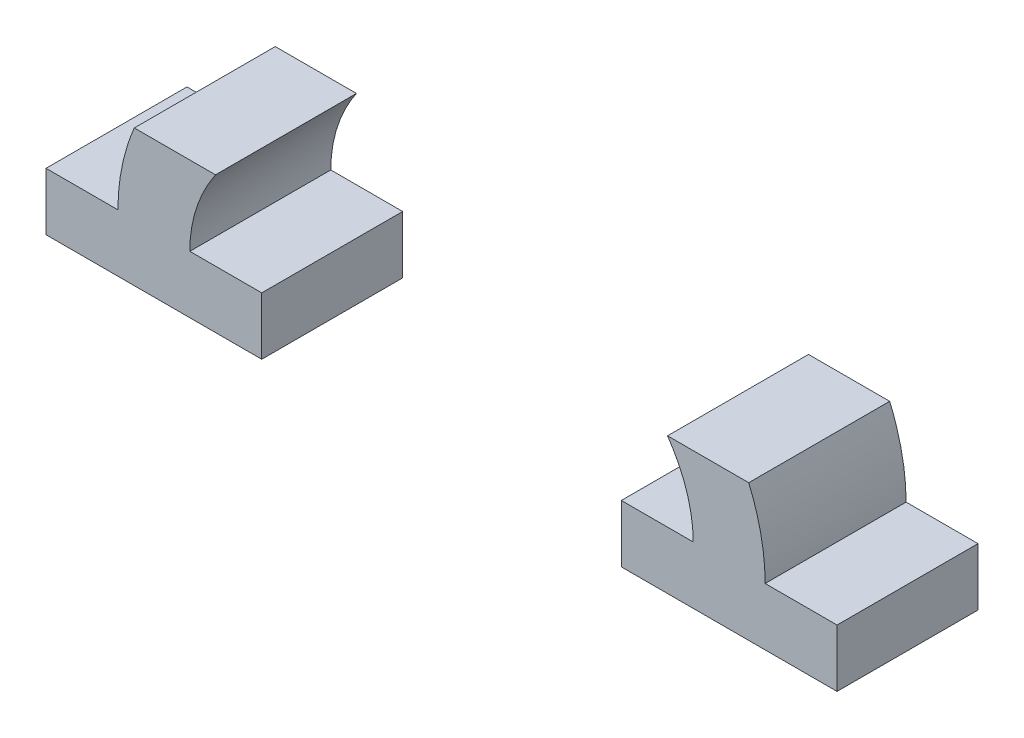
SolidWorks part; units mm, degrees
ref_plane "Front Plane" through (0, 0, 0) normal (0, 0, 1) x (1, 0, 0)
ref_plane "Top Plane" through (0, 0, 0) normal (0, 1, 0) x (1, 0, 0)
ref_plane "Right Plane" through (0, 0, 0) normal (1, 0, 0) x (0, 0, -1)
sketch "Sketch1" plane through (0, 0, 0) normal (0, 0, 1) x (1, 0, 0)
  line L0 (0, 51.691) -> (0, -47.0269) construction
  line L1 (-21.4685, 7.5) -> (-37.5, 7.5) construction
  line L2 (37.5, 7.5) -> (21.4685, 7.5) construction
  line L17 (21.3598, 7.5) -> (15.7146, 7.5)
  line L22 (-15.7146, 7.5) -> (-21.3598, 7.5)
  line L33 (-21.3177, 7.6) -> (-37.6, 7.6)
  line L34 (-27.5, 2) -> (-22.5004, 2)
  line L35 (-27.5, -2) -> (-27.5, 2)
  line L36 (-12.5, -2) -> (-27.5, -2)
  line L37 (-12.5, 2) -> (-12.5, -2)
  line L38 (-17.5006, 2) -> (-12.5, 2)
  line L39 (15.6458, 7.6) -> (-15.6458, 7.6)
  line L40 (12.5, 2) -> (17.5006, 2)
  line L41 (12.5, -2) -> (12.5, 2)
  line L42 (27.5, -2) -> (12.5, -2)
  line L43 (27.5, 2) -> (27.5, -2)
  line L44 (22.5004, 2) -> (27.5, 2)
  line L45 (37.6, 7.6) -> (21.3177, 7.6)
  line L46 (37.6, -7.6) -> (37.6, 7.6)
  line L47 (-37.6, -7.6) -> (37.6, -7.6)
  line L48 (-37.6, 7.6) -> (-37.6, -7.6)
  line L50 (-27.5, 2) -> (-22.5004, 2)
  line L51 (-27.5, -2) -> (-27.5, 2)
  line L52 (-12.5, -2) -> (-27.5, -2)
  line L53 (-12.5, 2) -> (-12.5, -2)
  line L54 (-17.5006, 2) -> (-12.5, 2)
  line L56 (12.5, 2) -> (17.5006, 2)
  line L57 (12.5, -2) -> (12.5, 2)
  line L58 (27.5, -2) -> (12.5, -2)
  line L59 (27.5, 2) -> (27.5, -2)
  line L60 (22.5004, 2) -> (27.5, 2)
  spline S8 degree 3 poles (-3020.5383, 97.1532) (36.7378, -43.2321) (-23.617, -18.6289) (-22.4681, 2.9598) (-22.449, 3.1992) (-22.3727, 3.9162) (-22.2969, 4.3904) (-22.0966, 5.3306) (-21.9726, 5.7945) (-21.7518, 6.4809) (-21.6726, 6.7075) (-14.7006, 25.1815) (39.0537, 25.8155) (-2808.2523, 1116.8382) knots -11.008157 -11.008157 -11.008157 -11.008157 0.125 0.125 0.25 0.25 0.5 0.5 0.75 0.75 0.875 0.875 11.031694 11.031694 11.031694 11.031694 only from (-22.5004, 2) to (-21.3177, 7.6)
  spline S9 degree 3 poles (-2529.0873, 1643.3154) (175.5446, -27.8045) (-0.3897, 37.4513) (-16.6507, 5.875) (-16.8469, 5.4159) (-17.1678, 4.4688) (-17.2911, 3.9845) (-17.416, 3.2445) (-17.4474, 2.9967) (-19.0735, -16.2527) (53.4109, -41.3788) (-3010.9453, 192.8327) knots -17.253037 -17.253037 -17.253037 -17.253037 0.25 0.25 0.5 0.5 0.75 0.75 0.875 0.875 10.431637 10.431637 10.431637 10.431637 only from (-15.6458, 7.6) to (-17.5006, 2)
  spline S10 degree 3 poles (3010.0197, 207.3949) (-53.6168, -41.8282) (19.0798, -16.2842) (17.4472, 2.9989) (17.4157, 3.247) (17.2902, 3.9887) (17.1665, 4.4736) (16.8442, 5.4229) (16.6476, 5.8816) (-0.028, 38.2338) (-190.5855, -20.223) (2626.566, 1482.401) knots -9.428366 -9.428366 -9.428366 -9.428366 0.125 0.125 0.25 0.25 0.5 0.5 0.75 0.75 18.820395 18.820395 18.820395 18.820395 only from (17.5006, 2) to (15.6458, 7.6)
  spline S11 degree 3 poles (2806.9501, 1120.0178) (-39.0325, 25.7625) (14.7006, 25.1817) (21.6726, 6.7075) (21.7518, 6.4808) (21.9726, 5.7944) (22.0967, 5.3305) (22.297, 4.3902) (22.3727, 3.9161) (22.449, 3.1991) (22.4681, 2.9598) (23.617, -18.6294) (-36.7384, -43.3101) (3020.4416, 100.9001) knots -10.031176 -10.031176 -10.031176 -10.031176 0.125 0.125 0.25 0.25 0.5 0.5 0.75 0.75 0.875 0.875 12.009101 12.009101 12.009101 12.009101 only from (21.3177, 7.6) to (22.5004, 2)
  spline S12 degree 3 poles (-22.5004, 2) (-22.4986, 2.2403) (-22.4936, 2.4804) (-22.4681, 2.9598) (-22.449, 3.1992) (-22.3727, 3.9162) (-22.2969, 4.3904) (-22.0966, 5.3306) (-21.9726, 5.7945) (-21.7518, 6.4809) (-21.6726, 6.7075) (-21.5158, 7.1229) (-21.4387, 7.3118) (-21.3598, 7.5) knots 0 0 0 0 0.125 0.125 0.25 0.25 0.5 0.5 0.75 0.75 0.875 0.875 0.981183 0.981183 0.981183 0.981183
  spline S13 degree 3 poles (-15.7146, 7.5) (-15.9733, 7.1204) (-16.2113, 6.7283) (-16.6507, 5.875) (-16.8469, 5.4159) (-17.1678, 4.4688) (-17.2911, 3.9845) (-17.416, 3.2445) (-17.4474, 2.9967) (-17.4894, 2.4996) (-17.4977, 2.25) (-17.5006, 2) knots 0.020234 0.020234 0.020234 0.020234 0.25 0.25 0.5 0.5 0.75 0.75 0.875 0.875 1 1 1 1
  spline S14 degree 3 poles (17.5006, 2) (17.4977, 2.2506) (17.4894, 2.5008) (17.4472, 2.9989) (17.4157, 3.247) (17.2902, 3.9887) (17.1665, 4.4736) (16.8442, 5.4229) (16.6476, 5.8816) (16.2108, 6.7289) (15.9735, 7.12) (15.7146, 7.5) knots 0 0 0 0 0.125 0.125 0.25 0.25 0.5 0.5 0.75 0.75 0.979789 0.979789 0.979789 0.979789
  spline S15 degree 3 poles (21.3598, 7.5) (21.4387, 7.3118) (21.5158, 7.1229) (21.6726, 6.7075) (21.7518, 6.4808) (21.9726, 5.7944) (22.0967, 5.3305) (22.297, 4.3902) (22.3727, 3.9161) (22.449, 3.1991) (22.4681, 2.9598) (22.4936, 2.4804) (22.4986, 2.2403) (22.5004, 2) knots 0.018816 0.018816 0.018816 0.018816 0.125 0.125 0.25 0.25 0.5 0.5 0.75 0.75 0.875 0.875 1 1 1 1
  dimension "D1" = 0.1
extrude "Boss-Extrude1" add sketch "Sketch1" along normal blind 9.8
